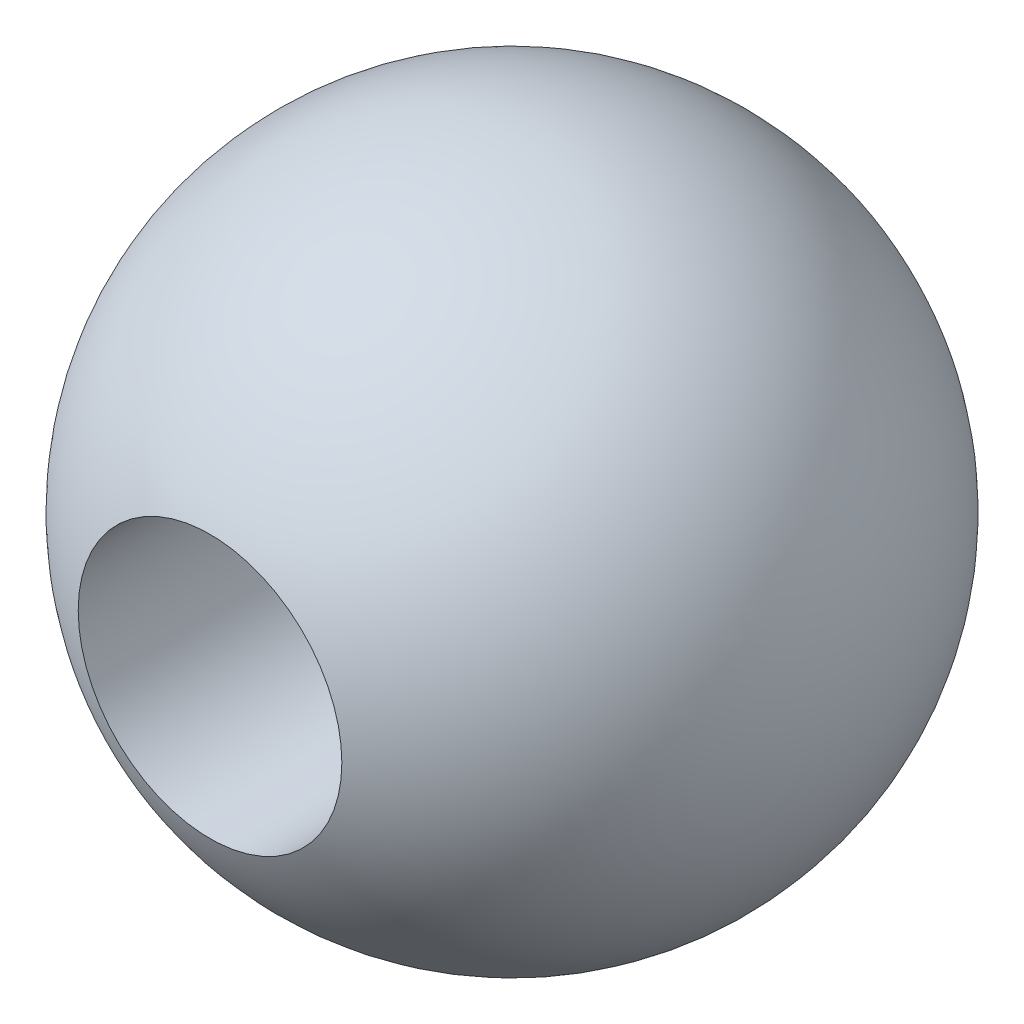
SolidWorks part; units mm, degrees
material "AISI 304"
ref_plane "Front" through (0, 0, 0) normal (0, 0, 1) x (1, 0, 0)
ref_plane "Top" through (0, 0, 0) normal (0, 1, 0) x (1, 0, 0)
ref_plane "Right" through (0, 0, 0) normal (1, 0, 0) x (0, 0, -1)
sketch "Sketch1" plane through (0, 0, 0) normal (0, 1, 0) x (1, 0, 0)
  line L0 (0, -5) -> (0, 5) construction
  line L1 (0, -5) -> (0, 5)
  arc A0 (0, 5) -> (0, -5) centre (0, 0) ccw
  dimension "D1" = 10
revolve "Revolve2" add sketch "Sketch1" angle 360 about L0
ref_plane "Plane1" through (0, 0, 5) normal (0, 0, 1) x (1, 0, 0)
sketch "Sketch2" plane through (0, 0, 5) normal (0, 0, 1) x (1, 0, 0)
  circle A0 centre (0, 0) radius 2
  dimension "D1" = 4
extrude "Cut-Extrude1" cut sketch "Sketch2" against normal blind 5
